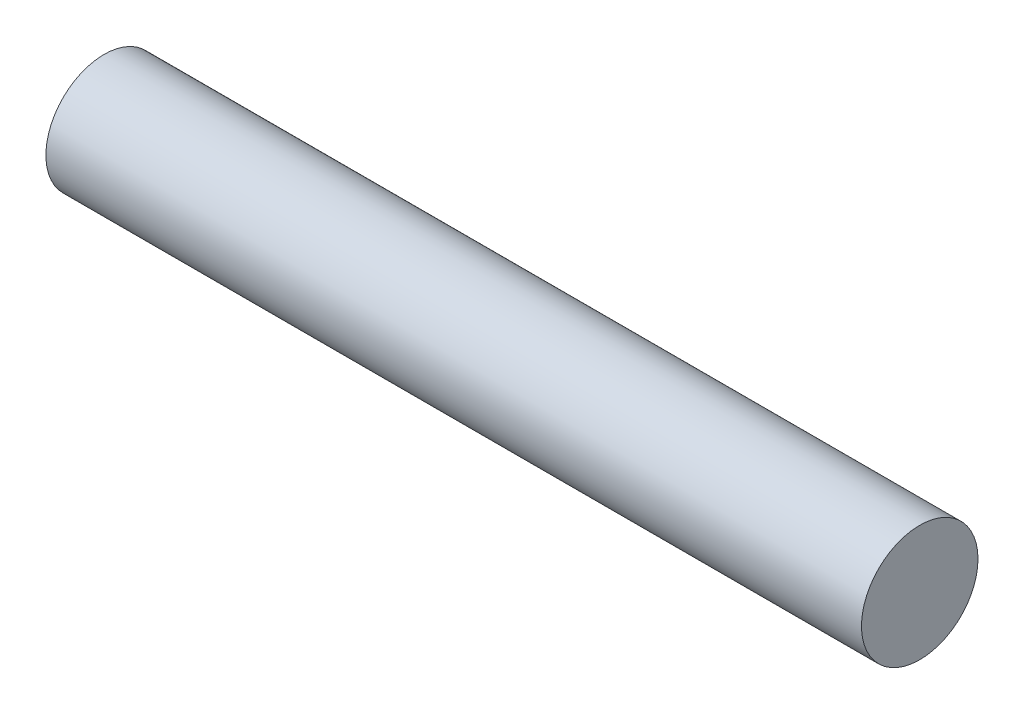
SolidWorks part; units mm, degrees
ref_plane "Front Plane" through (0, 0, 0) normal (0, 0, 1) x (1, 0, 0)
ref_plane "Top Plane" through (0, 0, 0) normal (0, 1, 0) x (1, 0, 0)
ref_plane "Right Plane" through (0, 0, 0) normal (1, 0, 0) x (0, 0, -1)
sketch "Sketch1" plane through (0, 0, 0) normal (1, 0, 0) x (0, 0, -1)
  circle A0 centre (0, 0) radius 1
  dimension "D1" = 2
extrude "Boss-Extrude1" add sketch "Sketch1" along normal blind 14
